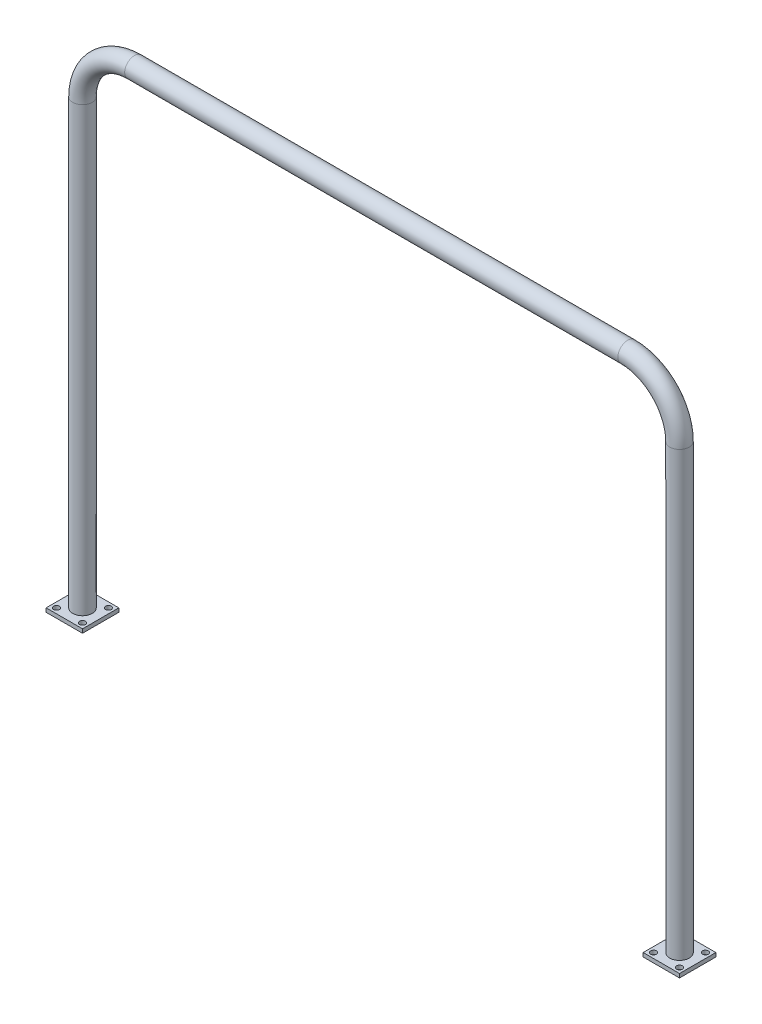
SolidWorks part; units mm, degrees
ref_plane "Front Plane" through (0, 0, 0) normal (0, 0, 1) x (1, 0, 0)
ref_plane "Top Plane" through (0, 0, 0) normal (0, 1, 0) x (1, 0, 0)
ref_plane "Right Plane" through (0, 0, 0) normal (1, 0, 0) x (0, 0, -1)
sketch "Sketch1" plane through (0, 0, 0) normal (0, 0, 1) x (1, 0, 0)
  line L0 (-460, 0) -> (-460, 682)
  line L1 (-380, 762) -> (380, 762)
  line L2 (460, 682) -> (460, 0)
  line L3 (0, 0) -> (0, 510.8066) construction
  line L4 (-460, 0) -> (460, 0) construction
  arc A0 (380, 762) -> (460, 682) centre (380, 682) cw
  arc A1 (-380, 762) -> (-460, 682) centre (-380, 682) ccw
  point P5 (0, 0)
  point P8 (0, 0)
  point P12 (460, 762)
  point P15 (-460, 762)
  dimension "D3" = 80
  dimension "D1" = 762
  dimension "D2" = 920
sketch "Sketch2" plane through (0, 0, 0) normal (0, 1, 0) x (1, 0, 0)
  circle A0 centre (-460, 0) radius 15
  dimension "D1" = 30
sweep "Sweep1" add profiles "Sketch2" path "Sketch1"
sketch "Sketch3" plane through (0, 0, 0) normal (0, -1, 0) x (1, 0, 0)
  line L1 (-480, -20) -> (-440, -20) construction
  line L2 (-480, -20) -> (-480, 20) construction
  line L3 (-480, 20) -> (-440, 20) construction
  line L4 (-440, -20) -> (-440, 20) construction
  line L5 (-480, -20) -> (-440, 20) construction
  line L6 (-480, 20) -> (-440, -20) construction
  line L7 (-488, -28) -> (-432, -28)
  line L8 (-488, -28) -> (-488, 28)
  line L9 (-488, 28) -> (-432, 28)
  line L10 (-432, -28) -> (-432, 28)
  line L11 (-488, -28) -> (-432, 28) construction
  line L12 (-488, 28) -> (-432, -28) construction
  point P0 (-460, 0)
  point P6 (-460, 0)
  point P12 (-432, 28)
  dimension "D1" = 40
  dimension "D2" = 8
extrude "Boss-Extrude1" add sketch "Sketch3" along normal blind 6 contours L9 L10 L7 L8
hole_wizard "M8 Clearance Hole1" positions "Sketch6" profile "Sketch7" hole size "M8" standard "ANSI Metric"
sketch "Sketch6" plane through (0, 0, 0) normal (0, 1, 0) x (1, 0, 0)
  line L1 (-480, 20) -> (-440, 20)
  line L2 (-480, 20) -> (-480, -20)
  line L3 (-480, -20) -> (-440, -20)
  line L4 (-440, 20) -> (-440, -20)
  line L5 (-480, 20) -> (-440, -20) construction
  line L6 (-480, -20) -> (-440, 20) construction
  circle A0 centre (-460, 0) radius 15 construction
  circle A1 centre (-460, 0) radius 15
  point P2 (-440, -20)
  point P65 (-480, 20)
  point P66 (-480, -20)
  point P67 (-440, 20)
  point P90 (-460, 0)
  dimension "D1" = 40
sketch "Sketch7" plane through (-440, 0, 20) normal (1, 0, 0) x (0, 0, 1)
  line L0 (0, 0) -> (0, 25.7039)
  line L1 (0, 25.7039) -> (4.5, 23)
  line L2 (4.5, 23) -> (4.5, 0)
  line L5 (4.5, 0) -> (0, 0)
  line L10 (0, 25.7039) -> (-4.5, 23) construction
  line L11 (0, -6.35) -> (0, 107.95) construction
  dimension "Hole Dia." = 9
  dimension "Hole Depth" = 23
  dimension "Drill Angle" = 118
mirror "Mirror1" about plane through (0, 0, 0) normal (1, 0, 0) of "M8 Clearance Hole1", "Boss-Extrude1"
